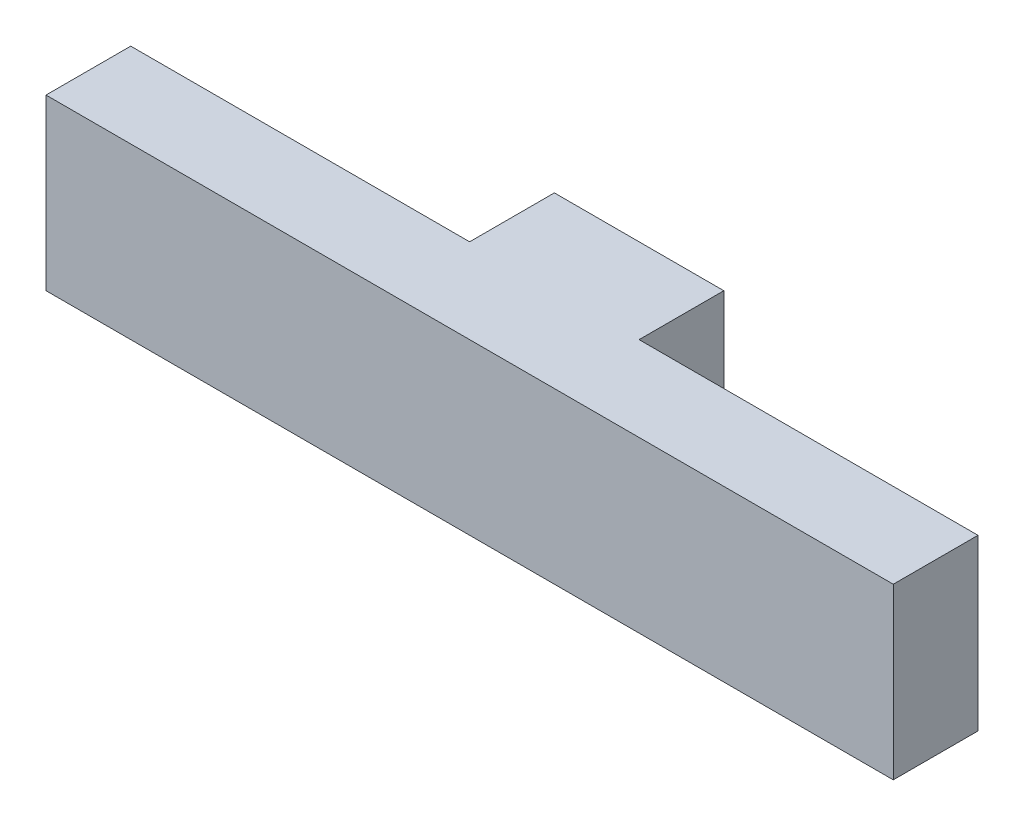
SolidWorks part; units mm, degrees
ref_plane "Přední rovina" through (0, 0, 0) normal (0, 0, 1) x (1, 0, 0)
ref_plane "Horní rovina" through (0, 0, 0) normal (0, 1, 0) x (1, 0, 0)
ref_plane "Pravá rovina" through (0, 0, 0) normal (1, 0, 0) x (0, 0, -1)
sketch "Sketch2" plane through (0, 0, 0) normal (0, 1, 0) x (1, 0, 0)
  line L0 (0, -20) -> (0, 0) construction
  line L1 (50, -20) -> (-50, -20)
  line L2 (50, -20) -> (50, -10)
  line L3 (50, -10) -> (10, -10)
  line L7 (-10, 0) -> (10, 0)
  line L8 (10, -10) -> (10, 0)
  line L9 (-10, -10) -> (-10, 0)
  line L10 (-50, -10) -> (-10, -10)
  line L11 (-50, -20) -> (-50, -10)
  dimension "D1" = 50
  dimension "D2" = 10
  dimension "D3" = 10
  dimension "D4" = 10
extrude "Boss-Extrude1" add sketch "Sketch2" along normal blind 20
